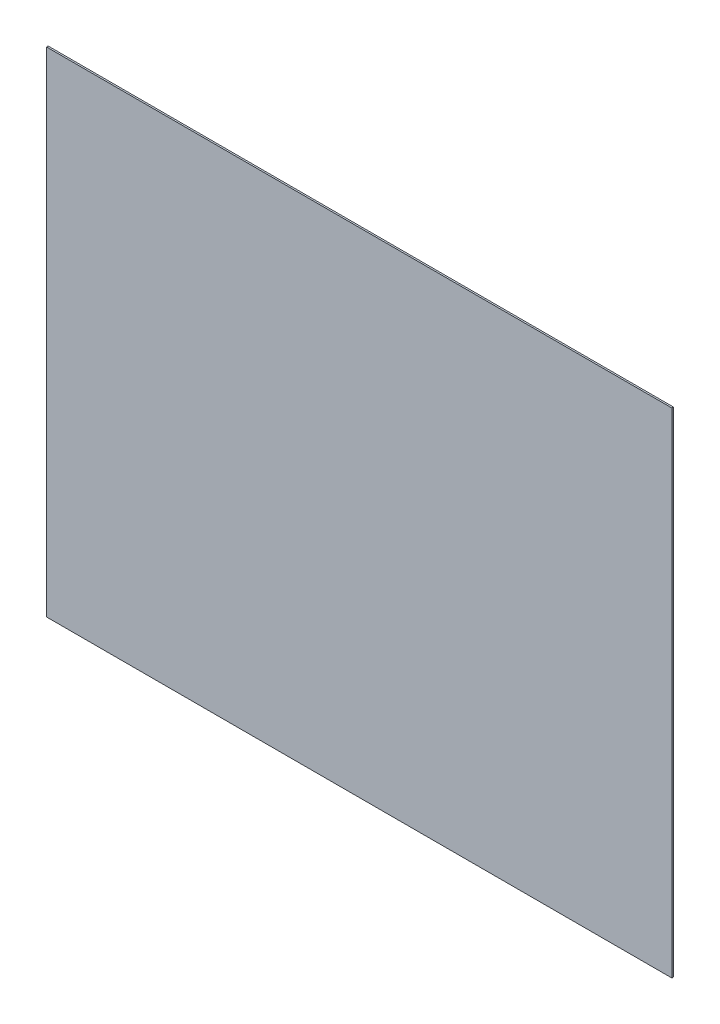
SolidWorks part; units mm, degrees
material "PBT General Purpose"
ref_plane "Alzado" through (0, 0, 0) normal (0, 0, 1) x (1, 0, 0)
ref_plane "Planta" through (0, 0, 0) normal (0, 1, 0) x (1, 0, 0)
ref_plane "Vista lateral" through (0, 0, 0) normal (1, 0, 0) x (0, 0, -1)
sketch "Croquis1" plane through (0, 0, 0) normal (0, 0, 1) x (1, 0, 0)
  line L1 (190, -150) -> (-190, -150)
  line L2 (190, -150) -> (190, 150)
  line L3 (190, 150) -> (-190, 150)
  line L4 (-190, -150) -> (-190, 150)
  line L5 (190, -150) -> (-190, 150) construction
  line L6 (190, 150) -> (-190, -150) construction
  point P0 (0, 0)
  dimension "D1" = 380
  dimension "D2" = 300
extrude "Saliente-Extruir1" add sketch "Croquis1" along normal blind 1
